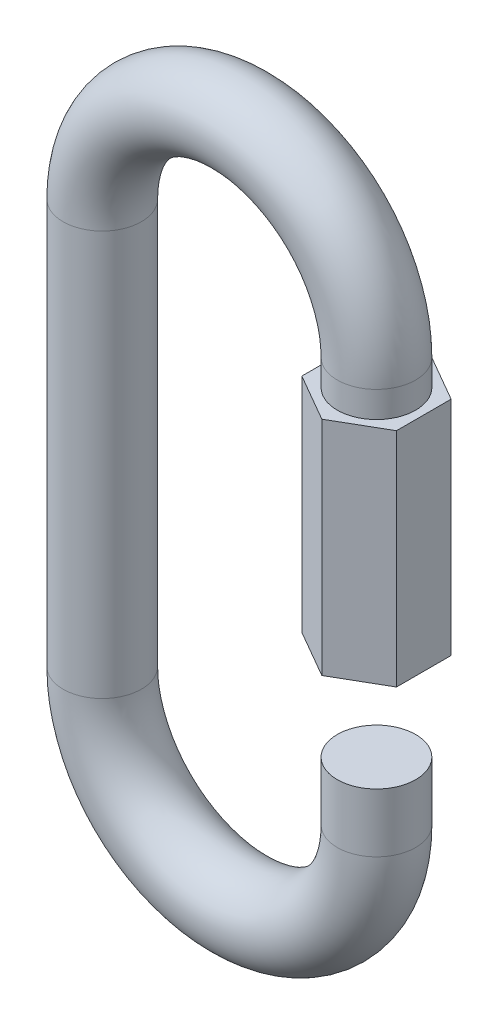
SolidWorks part; units mm, degrees
material "AISI 1020"
ref_plane "Front Plane" through (0, 0, 0) normal (0, 0, 1) x (1, 0, 0)
ref_plane "Top Plane" through (0, 0, 0) normal (0, 1, 0) x (1, 0, 0)
ref_plane "Right Plane" through (0, 0, 0) normal (1, 0, 0) x (0, 0, -1)
sketch "Sketch1" plane through (0, 0, 0) normal (0, 1, 0) x (1, 0, 0)
  circle A0 centre (0, 0) radius 3
  dimension "D1" = 6
sketch "Sketch2" plane through (0, 0, 0) normal (0, 0, 1) x (1, 0, 0)
  line L0 (0, 0) -> (0, 19)
  line L1 (3, 0) -> (-3, 0) construction
  line L2 (-21, 19) -> (-21, -12)
  line L3 (0, -12) -> (0, -7.5)
  arc A0 (0, 19) -> (-21, 19) centre (-10.5, 19) ccw
  arc A1 (-21, -12) -> (0, -12) centre (-10.5, -12) ccw
  point P9 (-10.5, 29.5)
  point P12 (-10.5, -22.5)
  point P15 (0, 19)
  dimension "D1" = 52
  dimension "D2" = 21
  dimension "D3" = 7.5
  dimension "D4" = 19
sweep "Sweep1" add profiles "Sketch1" path "Sketch2"
sketch "Sketch3" plane through (0, 0, 0) normal (0, -1, 0) x (1, 0, 0)
  line L1 (3.6233, 2.0919) -> (0, 4.1838)
  line L2 (0, 4.1838) -> (-3.6233, 2.0919)
  line L3 (-3.6233, 2.0919) -> (-3.6233, -2.0919)
  line L4 (-3.6233, -2.0919) -> (0, -4.1838)
  line L5 (0, -4.1838) -> (3.6233, -2.0919)
  line L6 (3.6233, -2.0919) -> (3.6233, 2.0919)
  circle A0 centre (0, 0) radius 3.6233 construction
extrude "Boss-Extrude1" add sketch "Sketch3" against normal blind 17
